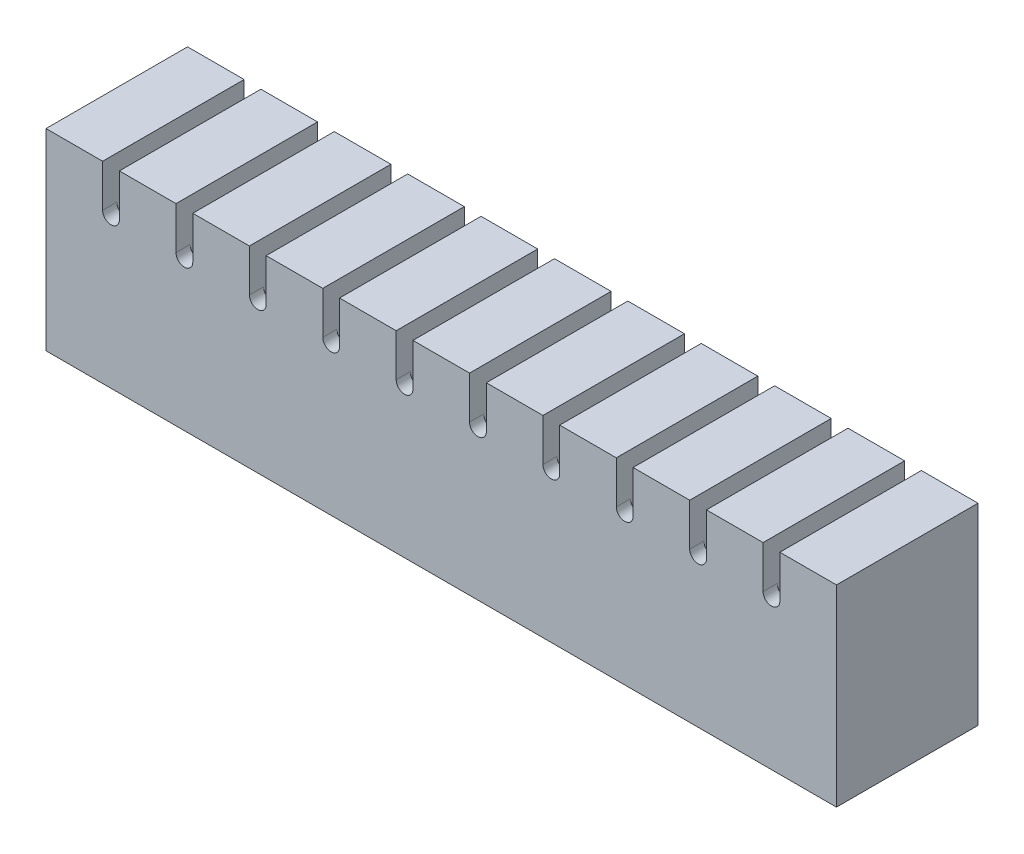
SolidWorks part; units mm, degrees
ref_plane "Ebene vorne" through (0, 0, 0) normal (0, 0, 1) x (1, 0, 0)
ref_plane "Ebene oben" through (0, 0, 0) normal (0, 1, 0) x (1, 0, 0)
ref_plane "Ebene rechts" through (0, 0, 0) normal (1, 0, 0) x (0, 0, -1)
sketch "Skizze1" plane through (0, 0, 0) normal (0, 0, 1) x (1, 0, 0)
  line L1 (0, 0) -> (55.85, 0)
  line L2 (0, 0) -> (0, -2)
  line L3 (0, -2) -> (55.85, -2)
  line L4 (55.85, 0) -> (55.85, -2)
  dimension "D1" = 55.85
  dimension "D2" = 2
extrude "Aufsatz-Linear austragen1" add sketch "Skizze1" along normal mid plane 10
sketch "Skizze2" plane through (0, 0, 0) normal (0, 0, 1) x (1, 0, 0)
  line L1 (0, 0) -> (4, 0)
  line L2 (0, 0) -> (0, 11.6)
  line L3 (0, 11.6) -> (4, 11.6)
  line L4 (4, 0) -> (4, 11.6)
  dimension "D1" = 11.6
  dimension "D2" = 4
extrude "Aufsatz-Linear austragen2" add sketch "Skizze2" along normal mid plane 10
pattern_linear "Lineares Muster1" count 11 spacing 5.185 along (1, 0, 0) of "Aufsatz-Linear austragen2"
sketch "Skizze3" plane through (0, 0, 5) normal (0, 0, 1) x (1, 0, 0)
  line L0 (4, 8.6) -> (4, 0)
  line L1 (4, 0) -> (4, 11.6) construction
  line L2 (4, 0) -> (5.185, 0)
  line L3 (5.185, 0) -> (5.185, 8.6)
  line L4 (5.185, 11.6) -> (5.185, 0) construction
  line L5 (4, 8.6) -> (5.185, 8.6) construction
  line L6 (9.185, 11.6) -> (5.185, 11.6) construction
  arc A0 (5.185, 8.6) -> (4, 8.6) centre (4.5925, 8.6) cw
  point P0 (0, 0)
  dimension "D1" = 3
extrude "Aufsatz-Linear austragen3" add sketch "Skizze3" against normal blind 1
mirror "Spiegeln1" about plane through (0, 0, 0) normal (0, 0, 1) of "Aufsatz-Linear austragen3"
pattern_linear "Lineares Muster2" count 10 spacing 5.185 along (1, 0, 0) of "Aufsatz-Linear austragen3", "Spiegeln1"
